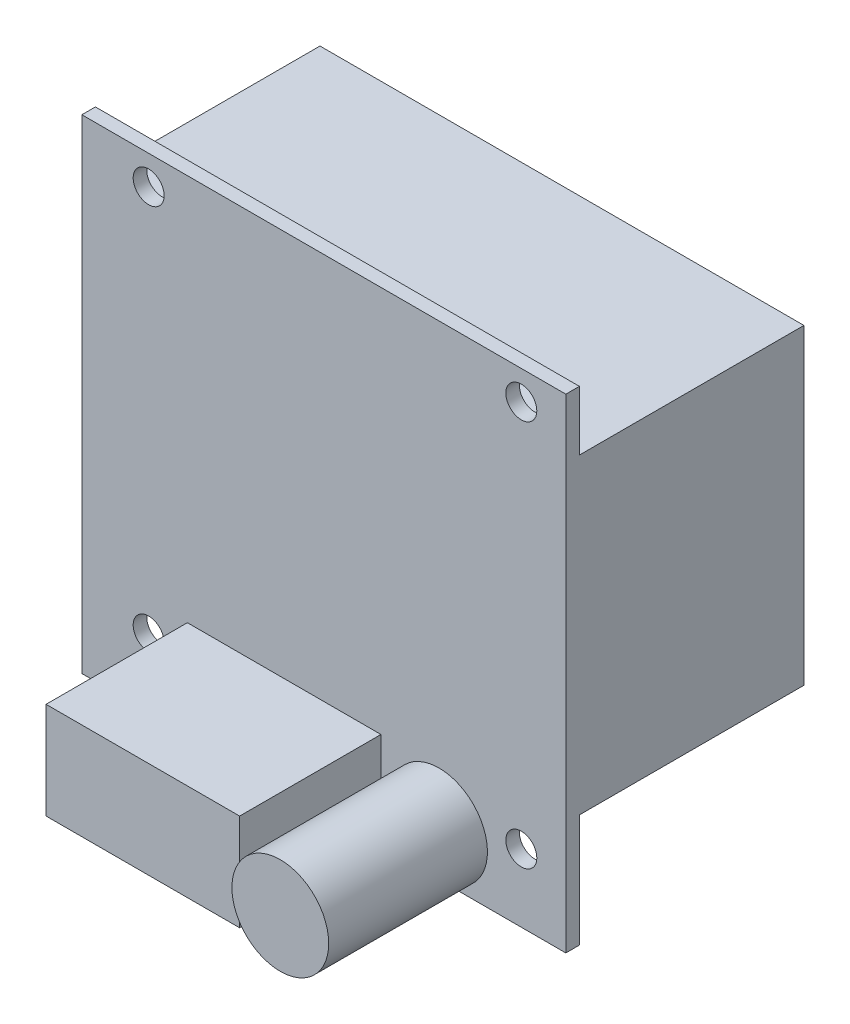
SolidWorks part; units mm, degrees
ref_plane "Alzado" through (0, 0, 0) normal (0, 0, 1) x (1, 0, 0)
ref_plane "Planta" through (0, 0, 0) normal (0, 1, 0) x (1, 0, 0)
ref_plane "Vista lateral" through (0, 0, 0) normal (1, 0, 0) x (0, 0, -1)
sketch "Croquis2" plane through (0, 0, 0) normal (0, 0, 1) x (1, 0, 0)
  line L1 (-25, -25) -> (25, -25)
  line L2 (-25, -25) -> (-25, 25)
  line L3 (-25, 25) -> (25, 25)
  line L4 (25, -25) -> (25, 25)
  line L5 (-25, -25) -> (25, 25) construction
  line L6 (-25, 25) -> (25, -25) construction
  point P0 (0, 0)
  dimension "D1" = 50
  dimension "D2" = 50
extrude "Saliente-Extruir1" add sketch "Croquis2" along normal blind 1.4
sketch "Croquis3" plane through (0, 0, 1.4) normal (0, 0, 1) x (1, 0, 0)
  line L0 (25, 22) -> (22, 22) construction
  line L1 (25, -25) -> (25, 25) construction
  line L2 (22, 22) -> (22, 25) construction
  line L3 (25, 25) -> (-25, 25) construction
  line L4 (22, 22) -> (20.4, 22) construction
  line L5 (20.4, 22) -> (20.4, 20.4) construction
  line L6 (20.4, 20.4) -> (20.4, -16.4) construction
  line L7 (20.4, -16.4) -> (20.4, -18) construction
  line L8 (20.4, 22) -> (-16.5, 22) construction
  line L9 (-16.5, 22) -> (-18.1, 22) construction
  line L10 (-18.1, 22) -> (-18.1, -18) construction
  line L11 (-18.1, -18) -> (20.4, -18) construction
  circle A0 centre (20.4, 22) radius 1.6
  circle A1 centre (20.4, -18) radius 1.6
  circle A2 centre (-18.1, 22) radius 1.6
  circle A3 centre (-18.1, -18) radius 1.6
  dimension "D8" = 3.2
  dimension "D1" = 3
  dimension "D2" = 3
  dimension "D3" = 1.6
  dimension "D4" = 36.8
  dimension "D5" = 1.6
  dimension "D6" = 36.9
  dimension "D7" = 1.6
extrude "Cortar-Extruir1" cut sketch "Croquis3" against normal blind 1.4
sketch "Croquis4" plane through (0, 0, 0) normal (0, 0, -1) x (-1, 0, 0)
  line L0 (-20.4, 22) -> (-20.4, 18.85) construction
  line L1 (-20.4, 18.85) -> (-25, 18.85) construction
  line L2 (-25, -25) -> (-25, 25) construction
  line L3 (25, 25) -> (25, -25) construction
  line L4 (-25, 18.85) -> (25, 18.85)
  line L5 (-25, 18.85) -> (-25, -13.35)
  line L6 (-25, -13.35) -> (25, -13.35)
  line L7 (25, 18.85) -> (25, -13.35)
  dimension "D1" = 3.15
  dimension "D2" = 32.2
extrude "Saliente-Extruir2" add sketch "Croquis4" along normal blind 23.2
sketch "Croquis5" plane through (0, 0, 1.4) normal (0, 0, 1) x (1, 0, 0)
  line L0 (-18.1, -18) -> (-14.1, -18) construction
  line L1 (-14.1, -18) -> (-14.1, -25)
  line L2 (-25, -25) -> (25, -25) construction
  line L3 (-14.1, -25) -> (5.9, -25)
  line L4 (5.9, -25) -> (5.9, -15)
  line L5 (5.9, -15) -> (-14.1, -15)
  line L6 (-14.1, -15) -> (-14.1, -18)
  dimension "D1" = 4
  dimension "D2" = 20
  dimension "D3" = 10
extrude "Saliente-Extruir3" add sketch "Croquis5" along normal blind 14.6
sketch "Croquis6" plane through (0, 0, 1.4) normal (0, 0, 1) x (1, 0, 0)
  line L0 (11.9, -25) -> (11.9, -20) construction
  line L1 (5.9, -25) -> (25, -25) construction
  line L2 (11.9, -20) -> (5.9, -20) construction
  line L3 (5.9, -25) -> (5.9, -15) construction
  circle A0 centre (11.9, -20) radius 5
  dimension "D1" = 5
  dimension "D2" = 6
extrude "Saliente-Extruir4" add sketch "Croquis6" along normal blind 16.4
